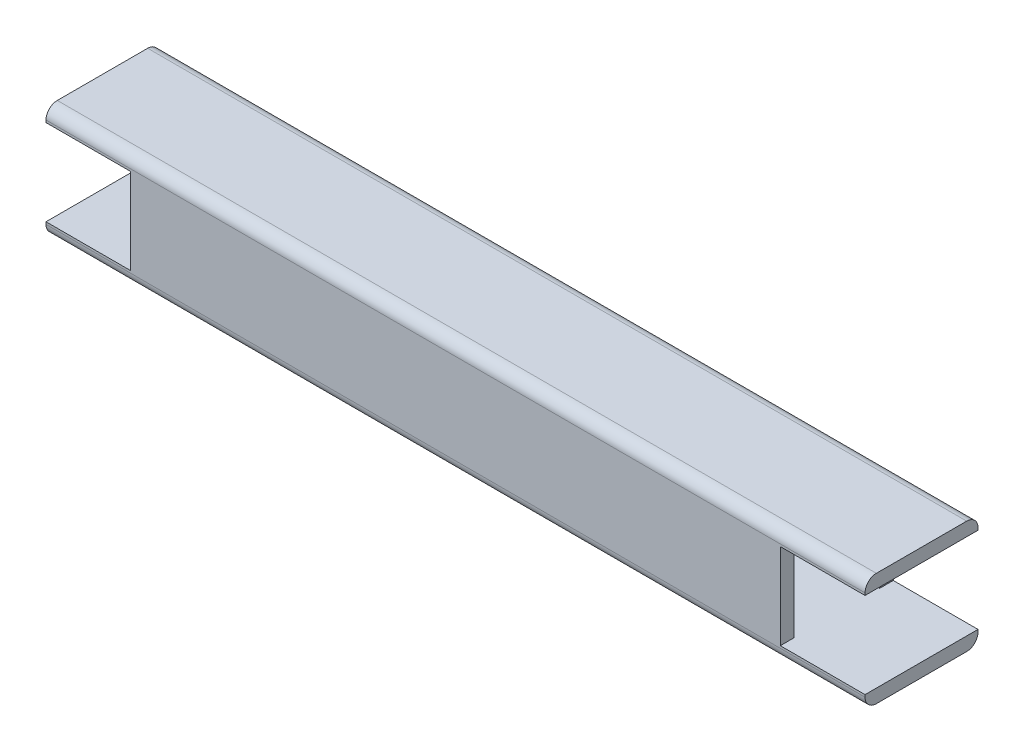
SolidWorks part; units mm, degrees
material "Plain Carbon Steel"
ref_plane "Front Plane" through (0, 0, 0) normal (0, 0, 1) x (1, 0, 0)
ref_plane "Top Plane" through (0, 0, 0) normal (0, 1, 0) x (1, 0, 0)
ref_plane "Right Plane" through (0, 0, 0) normal (1, 0, 0) x (0, 0, -1)
sketch "Sketch1" plane through (0, 0, 0) normal (1, 0, 0) x (0, 0, -1)
  line L0 (0, 2.54) -> (0, 22.86)
  line L1 (-2.54, 25.4) -> (-22.86, 25.4)
  line L2 (-25.4, 22.86) -> (-25.4, 2.54)
  line L3 (-22.86, 0) -> (-2.54, 0)
  line L4 (-3.048, 3.048) -> (-3.048, 22.352)
  line L5 (-3.048, 22.352) -> (-22.352, 22.352)
  line L6 (-22.352, 22.352) -> (-22.352, 3.048)
  line L7 (-22.352, 3.048) -> (-3.048, 3.048)
  arc A0 (-25.4, 2.54) -> (-22.86, 0) centre (-22.86, 2.54) ccw
  arc A1 (0, 2.54) -> (-2.54, 0) centre (-2.54, 2.54) cw
  arc A2 (0, 22.86) -> (-2.54, 25.4) centre (-2.54, 22.86) ccw
  arc A3 (-25.4, 22.86) -> (-22.86, 25.4) centre (-22.86, 22.86) cw
  arc A4 (-3.048, 22.352) -> (-3.048, 22.352) centre (-3.048, 22.352) ccw
  arc A5 (-22.352, 22.352) -> (-22.352, 22.352) centre (-22.352, 22.352) cw
  arc A6 (-22.352, 3.048) -> (-22.352, 3.048) centre (-22.352, 3.048) ccw
  arc A7 (-3.048, 3.048) -> (-3.048, 3.048) centre (-3.048, 3.048) cw
  point P12 (0, 0)
  point P15 (0, 25.4)
  point P18 (-25.4, 25.4)
  dimension "D3" = 2.54
  dimension "D1" = 25.4
  dimension "D2" = 25.4
  dimension "D4" = 3.048
extrude "Boss-Extrude1" add sketch "Sketch1" along normal blind 184.15
sketch "Sketch2" plane through (184.15, 0, 0) normal (1, 0, 0) x (0, 0, -1)
  line L0 (-25.4, 22.86) -> (-25.4, 2.54) construction
  line L1 (-25.4, 22.352) -> (0, 22.352)
  line L2 (-25.4, 22.352) -> (-25.4, 3.048)
  line L3 (-25.4, 3.048) -> (0, 3.048)
  line L4 (0, 22.352) -> (0, 3.048)
  line L5 (-12.7, 3.048) -> (-12.7, 22.352) construction
  line L6 (-25.4, 12.7) -> (0, 12.7) construction
  line L7 (0, 2.54) -> (0, 22.86) construction
  line L8 (-3.048, 22.352) -> (-22.352, 22.352) construction
  line L9 (-22.352, 3.048) -> (-3.048, 3.048) construction
  point P1148 (-12.7, 12.7)
extrude "Cut-Extrude1" cut sketch "Sketch2" against normal blind 19.05
sketch "Sketch3" plane through (0, 0, 0) normal (-1, 0, 0) x (0, 0, 1)
  line L0 (0, 2.54) -> (0, 22.86) construction
  line L1 (0, 22.352) -> (25.4, 22.352)
  line L2 (0, 22.352) -> (0, 3.048)
  line L3 (0, 3.048) -> (25.4, 3.048)
  line L4 (25.4, 22.352) -> (25.4, 3.048)
  line L5 (12.7, 3.048) -> (12.7, 22.352) construction
  line L6 (0, 12.7) -> (25.4, 12.7) construction
  line L7 (25.4, 22.86) -> (25.4, 2.54) construction
  line L8 (3.048, 22.352) -> (22.352, 22.352) construction
  line L9 (22.352, 3.048) -> (3.048, 3.048) construction
  point P248 (12.7, 12.7)
extrude "Cut-Extrude2" cut sketch "Sketch3" against normal blind 19.05
